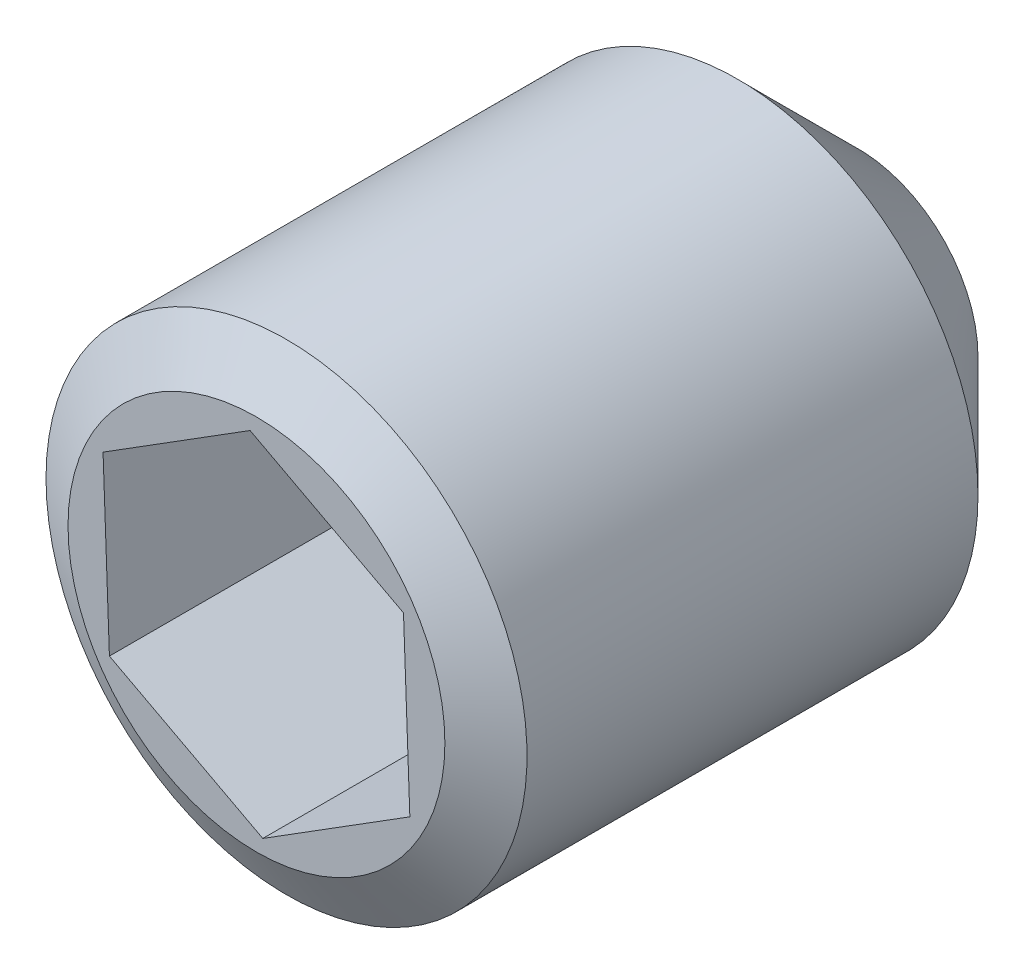
SolidWorks part; units mm, degrees
ref_plane "Plano frontal" through (0, 0, 0) normal (0, 0, 1) x (1, 0, 0)
ref_plane "Plano superior" through (0, 0, 0) normal (0, 1, 0) x (1, 0, 0)
ref_plane "Plano direito" through (0, 0, 0) normal (1, 0, 0) x (0, 0, -1)
sketch "Esboço1" plane through (0, 0, 0) normal (0, 0, 1) x (1, 0, 0)
  circle A0 centre (0, 0) radius 4
  dimension "D1" = 8
extrude "Ressalto-extrusão1" add sketch "Esboço1" along normal blind 10
cosmetic thread "Representação de rosca1" parameters "D2"=6.619
sketch "Esboço2" plane through (0, 0, 10) normal (0, 0, 1) x (1, 0, 0)
  line L1 (-0.1058, 2.8848) -> (-2.5512, 1.3508)
  line L2 (-2.5512, 1.3508) -> (-2.4454, -1.534)
  line L3 (-2.4454, -1.534) -> (0.1058, -2.8848)
  line L4 (0.1058, -2.8848) -> (2.5512, -1.3508)
  line L5 (2.5512, -1.3508) -> (2.4454, 1.534)
  line L6 (2.4454, 1.534) -> (-0.1058, 2.8848)
  circle A0 centre (0, 0) radius 2.5 construction
  dimension "D1" = 5
extrude "Corte-extrusão1" cut sketch "Esboço2" against normal blind 6
chamfer "Chanfro3" distance 0.5 angle 60 1 edges at (4, 0, 10)
chamfer "Chanfro4" distance 2 angle 45 1 edges at (4, 0, 0)
